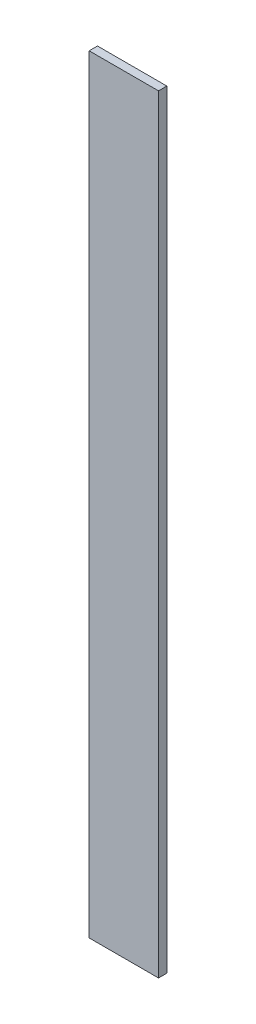
SolidWorks part; units mm, degrees
ref_plane "Front Plane" through (0, 0, 0) normal (0, 0, 1) x (1, 0, 0)
ref_plane "Top Plane" through (0, 0, 0) normal (0, 1, 0) x (1, 0, 0)
ref_plane "Right Plane" through (0, 0, 0) normal (1, 0, 0) x (0, 0, -1)
sketch "Sketch1" plane through (0, 0, 0) normal (0, 0, 1) x (1, 0, 0)
  line L1 (-12.5, 138.5) -> (12.5, 138.5)
  line L2 (-12.5, 138.5) -> (-12.5, -138.5)
  line L3 (-12.5, -138.5) -> (12.5, -138.5)
  line L4 (12.5, 138.5) -> (12.5, -138.5)
  line L5 (-12.5, 138.5) -> (12.5, -138.5) construction
  line L6 (-12.5, -138.5) -> (12.5, 138.5) construction
  point P0 (0, 0)
  dimension "D1" = 25
  dimension "D2" = 277
extrude "Boss-Extrude1" add sketch "Sketch1" along normal blind 3
equation "\"PCLength\"= 320mm'Length across I/O from PS to GPU"
equation "\"PCWidth\"= 242mm'Distance of longest part parallel to GPU(ussually GPU)"
equation "\"PCHeight\"= 172mm'Tallest point with mobo laying flat"
equation "\"WallThickness\"= 9mm'Thickness of each outer tank wall"
equation "\"ThermoBarrierThickness\"= 3mm'Thickness of barrier between hot side and cold side"
equation "\"HotSideGap\"= 25mm'Space in the hot side for a pump"
equation "\"PCClearance\"= 30mm'Clearance from top of tank to top of PC"
equation "\"RadiatorHeight\"= 275mm'Final Height from ground of radiators"
equation "\"AirflowGap\"= 36mm'Distance between radiators and tank for airflow"
equation "\"VolumeSubtraction\"= 230mm"
equation "\"D1@Sketch1\"=\"HotSideGap\""
equation "\"D2@Sketch1\"=\"RadiatorHeight\" + 5 - \"ThermoBarrierThickness\""
equation "\"D1@Boss-Extrude1\"=\"ThermoBarrierThickness\""
